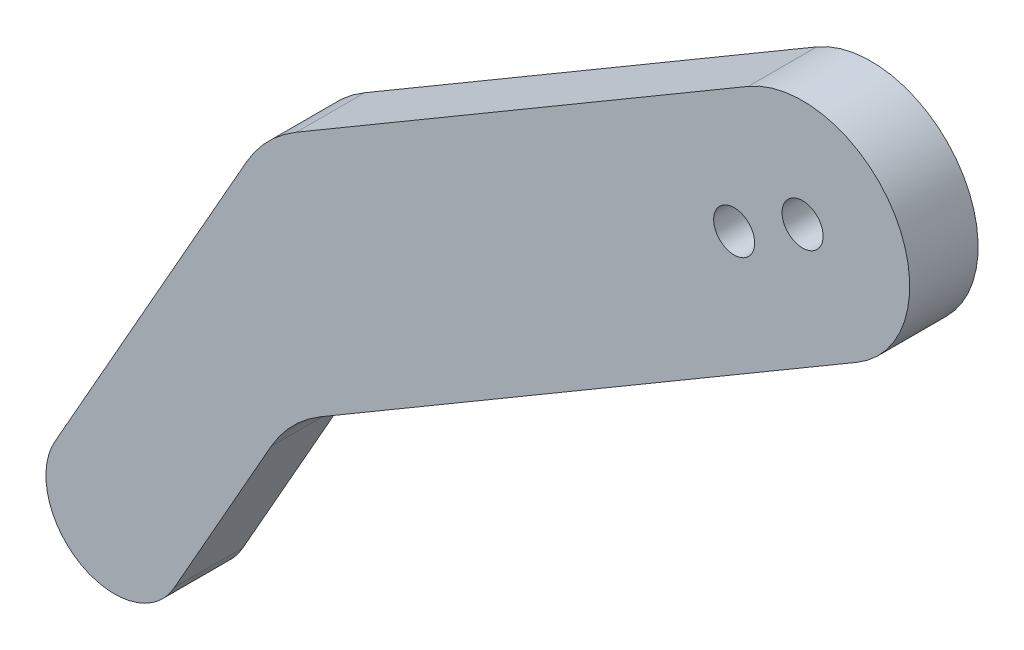
SolidWorks part; units mm, degrees
ref_plane "Front Plane" through (0, 0, 0) normal (0, 0, 1) x (1, 0, 0)
ref_plane "Top Plane" through (0, 0, 0) normal (0, 1, 0) x (1, 0, 0)
ref_plane "Right Plane" through (0, 0, 0) normal (1, 0, 0) x (0, 0, -1)
sketch "Sketch3" plane through (0, 0, 0) normal (0, 0, 1) x (1, 0, 0)
  line L0 (0, 0) -> (13.9676, 24.6365)
  line L1 (0, 0) -> (8.6992, -4.932) construction
  line L2 (8.6992, -4.932) -> (15.762, 7.5257)
  line L3 (17.599, 28.3254) -> (50.6344, 47.7451)
  line L4 (50.6344, 47.7451) -> (58.5705, 34.2448) construction
  line L5 (19.3935, 11.2145) -> (58.5705, 34.2448)
  arc A0 (50.6344, 47.7451) -> (58.5705, 34.2448) centre (54.6024, 40.995) cw
  arc A1 (0, 0) -> (8.6992, -4.932) centre (4.3053, -2.5441) ccw
  arc A2 (13.9676, 24.6365) -> (17.599, 28.3254) centre (22.6668, 19.7046) cw
  arc A3 (15.762, 7.5257) -> (19.3935, 11.2145) centre (24.4612, 2.5937) cw
  point P10 (15.2891, 26.9675)
  point P13 (19.9017, -5.697)
  point P15 (17.0835, 9.8566)
  dimension "D7" = 5.0008
  dimension "D8" = 10
  dimension "D9" = 10
  dimension "D1" = 31
  dimension "D2" = 41
  dimension "D3" = 150
  dimension "D5" = 17
  dimension "D6" = 10
extrude "Boss-Extrude1" add sketch "Sketch3" along normal blind 5 contours L0 A1 L2 L5 A0 L3
sketch "Sketch4" plane through (0, 0, 5) normal (0, 0, 1) x (1, 0, 0)
  line L0 (50.6344, 47.7451) -> (58.5705, 34.2448) construction
  line L1 (54.6024, 40.995) -> (22.5812, 22.1713) construction
  line L2 (50.6344, 47.7451) -> (58.5705, 34.2448) construction
  circle A0 centre (54.6024, 40.995) radius 1.5
  arc A1 (58.5705, 34.2448) -> (50.6344, 47.7451) centre (54.6024, 40.995) ccw construction
  circle A2 centre (49.6024, 38.0557) radius 1.5
  point P9 (54.6024, 40.995)
  dimension "D1" = 3
  dimension "D2" = 5
  dimension "D3" = 3
extrude "Cut-Extrude1" cut sketch "Sketch4" against normal blind 7
